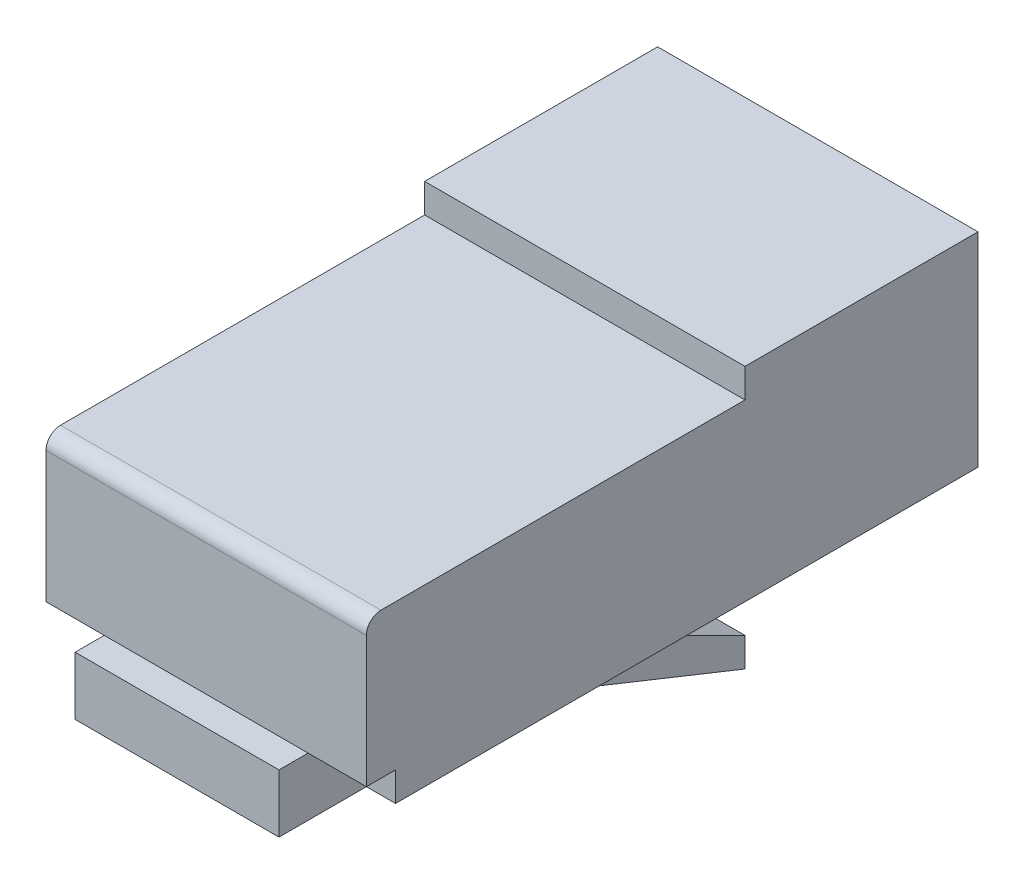
SolidWorks part; units mm, degrees
ref_plane "Спереди" through (0, 0, 0) normal (0, 0, 1) x (1, 0, 0)
ref_plane "Сверху" through (0, 0, 0) normal (0, 1, 0) x (1, 0, 0)
ref_plane "Справа" through (0, 0, 0) normal (1, 0, 0) x (0, 0, -1)
sketch "Эскиз2" plane through (0, 0, 0) normal (0, 0, 1) x (1, 0, 0)
  line L1 (11, 6) -> (0, 6)
  line L2 (11, 6) -> (11, 0)
  line L3 (11, 0) -> (0, 0)
  line L4 (0, 6) -> (0, 0)
  dimension "D1" = 11
  dimension "D2" = 6
extrude "Бобышка-Вытянуть1" add sketch "Эскиз2" along normal blind 5
sketch "Эскиз3" plane through (0, 0, 0) normal (0, 0, -1) x (-1, 0, 0)
  line L1 (-11, 6) -> (0, 6)
  line L2 (-11, 6) -> (-11, 0)
  line L3 (-11, 0) -> (0, 0)
  line L4 (0, 6) -> (0, 0)
extrude "Бобышка-Вытянуть2" add sketch "Эскиз3" along normal blind 8
sketch "Эскиз4" plane through (0, 0, -8) normal (0, 0, -1) x (-1, 0, 0)
  line L0 (0, 6) -> (-11, 6) construction
  line L1 (-11, 0) -> (0, 0)
  line L2 (-11, 0) -> (-11, 7)
  line L3 (-11, 7) -> (0, 7)
  line L4 (0, 0) -> (0, 7)
  dimension "D1" = 1
extrude "Бобышка-Вытянуть3" add sketch "Эскиз4" along normal blind 8
sketch "Эскиз6" plane through (0, 0, 5) normal (0, 0, 1) x (1, 0, 0)
  line L0 (2, -1) -> (2, 1)
  line L2 (2, 1) -> (9, 1)
  line L3 (9, 1) -> (9, -1)
  line L4 (9, -1) -> (2, -1)
  line L5 (0, 6) -> (0, 0) construction
  line L6 (11, 0) -> (11, 6) construction
  line L7 (0, 0) -> (11, 0) construction
  dimension "D1" = 2
  dimension "D2" = 2
  dimension "D3" = 1
  dimension "D4" = 1
extrude "Бобышка-Вытянуть4" add sketch "Эскиз6" along normal blind 1
sketch "Эскиз8" plane through (0, 0, 5) normal (0, 0, 1) x (1, 0, 0)
  line L0 (11, 0) -> (11, 6) construction
  line L1 (2, 1) -> (0, 1)
  line L2 (2, 1) -> (2, 0)
  line L3 (2, 0) -> (0, 0)
  line L4 (0, 1) -> (0, 0)
  line L5 (9, 0) -> (11, 0)
  line L6 (9, 0) -> (9, 1)
  line L7 (9, 1) -> (11, 1)
  line L8 (11, 0) -> (11, 1)
extrude "Вырез-Вытянуть1" cut sketch "Эскиз8" against normal blind 1
sketch "Эскиз10" plane through (0, 0, 0) normal (0, -1, 0) x (1, 0, 0)
  line L0 (9, 5) -> (9, 2)
  line L1 (2, 5) -> (2, 2)
  line L2 (9, 2) -> (2, 2)
  line L3 (2, 5) -> (9, 5) construction
  line L12 (11, 4) -> (9, 4)
  line L13 (9, 4) -> (9, 5)
  line L14 (9, 5) -> (2, 5)
  line L15 (2, 5) -> (2, 4)
  line L16 (2, 4) -> (0, 4)
  line L17 (0, 4) -> (0, -16)
  line L18 (0, -16) -> (11, -16)
  line L19 (11, -16) -> (11, 4)
  line L22 (9, 5) -> (2, 5)
  dimension "D1" = 3
  dimension "D2" = 0
extrude "Бобышка-Вытянуть5" add sketch "Эскиз10" along normal blind 1
sketch "Эскиз12" plane through (9, 0, 0) normal (1, 0, 0) x (0, 0, -1)
  line L0 (-2, 0) -> (1, -0.5)
  line L1 (1, -0.5) -> (1, -2)
  line L2 (1, -2) -> (0, -1.5)
  line L3 (0, -1.5) -> (-2, -1)
  line L4 (-2, -1) -> (-2, 0)
extrude "Бобышка-Вытянуть6" add sketch "Эскиз12" against normal blind 7
ref_plane "Плоскость1" through (8, 0, 0) normal (1, 0, 0) x (0, 0, -1)
sketch "Эскиз13" plane through (8, 0, 0) normal (1, 0, 0) x (0, 0, -1)
  line L0 (1, -0.5) -> (6, -1.5)
  line L1 (6, -1.5) -> (11, -4)
  line L2 (11, -4) -> (11, -5)
  line L3 (11, -5) -> (6, -3)
  line L4 (6, -3) -> (1, -2)
  line L5 (1, -2) -> (1, -0.5) construction
  line L6 (-4, 0) -> (16, 0) construction
  line L7 (1, -2) -> (1, -0.5)
  line L8 (16, 7) -> (16, 0) construction
  dimension "D1" = 5
  dimension "D2" = 5
extrude "Бобышка-Вытянуть7" add sketch "Эскиз13" against normal blind 5
sketch "Эскиз14" plane through (0, 0, -16) normal (0, 0, -1) x (-1, 0, 0)
  line L0 (0, 7) -> (-11, 7) construction
  line L1 (-9, 2) -> (-2, 2)
  line L2 (-9, 2) -> (-9, 5)
  line L3 (-9, 5) -> (-2, 5)
  line L4 (-2, 2) -> (-2, 5)
  line L5 (-11, 0) -> (0, 0) construction
  line L6 (-11, 7) -> (-11, 0) construction
  line L7 (0, 0) -> (0, 7) construction
  dimension "D1" = 2
  dimension "D2" = 2
  dimension "D3" = 2
  dimension "D4" = 2
extrude "Вырез-Вытянуть2" cut sketch "Эскиз14" against normal blind 8
fillet "Скругление1" radius 0.5 1 edges at (5.5, 6, 5)
